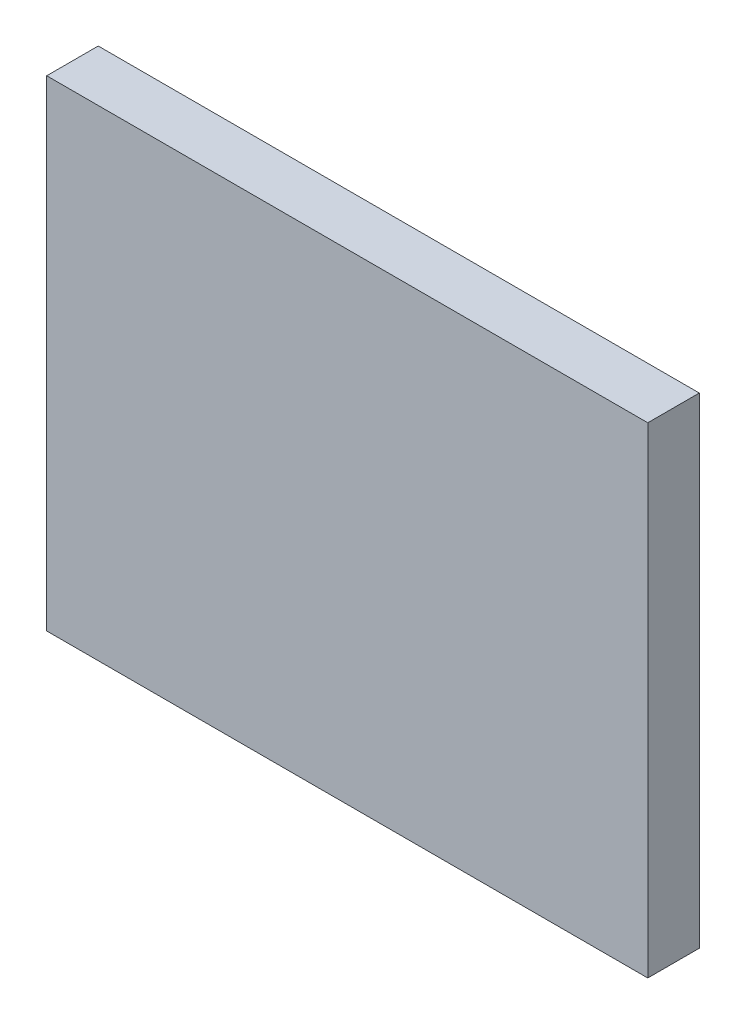
SolidWorks part; units mm, degrees
ref_plane "Plan de face" through (0, 0, 0) normal (0, 0, 1) x (1, 0, 0)
ref_plane "Plan de dessus" through (0, 0, 0) normal (0, 1, 0) x (1, 0, 0)
ref_plane "Plan de droite" through (0, 0, 0) normal (1, 0, 0) x (0, 0, -1)
sketch "Esquisse1" plane through (0, 0, 0) normal (0, 0, 1) x (1, 0, 0)
  line L1 (0, 0) -> (350, 0)
  line L2 (0, 0) -> (0, 280)
  line L3 (0, 280) -> (350, 280)
  line L4 (350, 0) -> (350, 280)
  dimension "D1" = 350
  dimension "D2" = 280
extrude "Boss.-Extru.1" add sketch "Esquisse1" along normal blind 30
